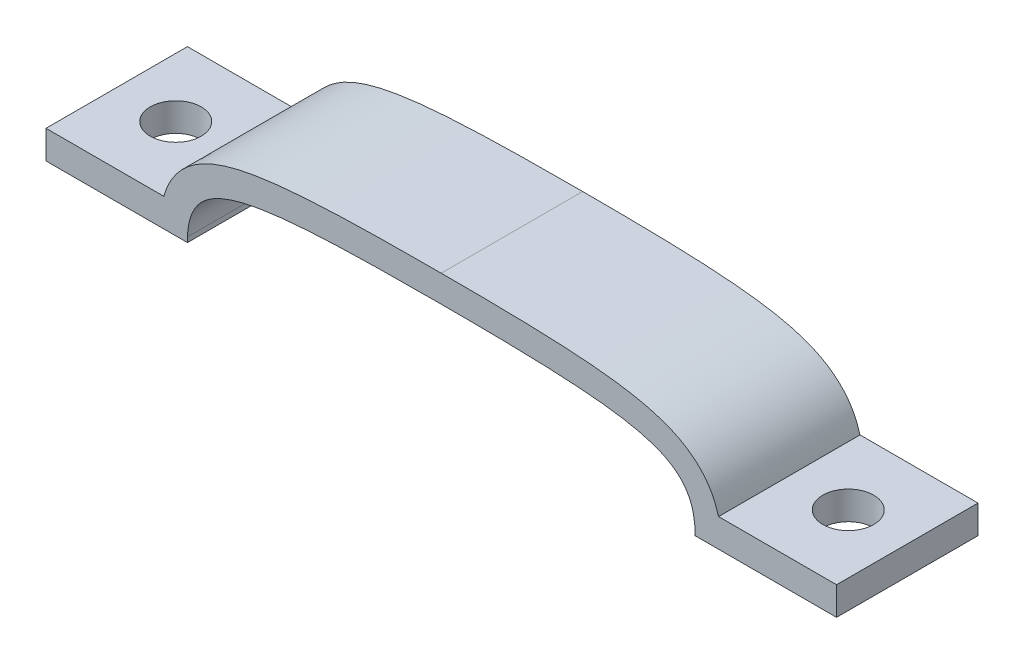
SolidWorks part; units mm, degrees
ref_plane "Front Plane" through (0, 0, 0) normal (0, 0, 1) x (1, 0, 0)
ref_plane "Top Plane" through (0, 0, 0) normal (0, 1, 0) x (1, 0, 0)
ref_plane "Right Plane" through (0, 0, 0) normal (1, 0, 0) x (0, 0, -1)
sketch "Sketch1" plane through (0, 0, 0) normal (0, 0, 1) x (1, 0, 0)
  line L1 (-24.3792, 158.0869) -> (-59.8719, 158.0869) construction
  line L2 (-59.8719, 158.4295) -> (-59.8719, 158.0869) construction
  line L3 (-60.0719, 158.4339) -> (-60.0719, 158.0869)
  line L4 (-60.0719, 158.0869) -> (-70.0719, 158.0869)
  line L5 (-24.1792, 158.0869) -> (-14.1792, 158.0869)
  line L8 (-70.0719, 158.0869) -> (-70.0719, 160.0869)
  line L9 (-22.5208, 160.0869) -> (-14.1792, 160.0869)
  line L10 (-70.0719, 160.0869) -> (-61.7376, 160.0869)
  line L11 (-14.1792, 158.0869) -> (-14.1792, 160.0869)
  spline S2 degree 3 poles (-24.3792, 158.0869) (-24.3792, 158.298) (-24.3948, 158.7203) (-24.4847, 159.3508) (-24.6697, 159.9591) (-25.0702, 160.7158) (-25.8681, 161.4447) (-27.0347, 161.9787) (-28.2637, 162.3243) (-29.5199, 162.5549) (-30.7848, 162.7171) (-32.0543, 162.832) (-33.324, 162.9151) (-34.5929, 162.9748) (-35.8594, 163.0175) (-37.1228, 163.0472) (-38.3821, 163.067) (-39.6369, 163.0793) (-40.8865, 163.0857) (-41.7157, 163.0869) (-42.1292, 163.0869) (-42.1292, 163.0869) knots 0.755163 0.755163 0.755163 0.755163 0.762814 0.770465 0.778117 0.785768 0.80107 0.816372 0.831675 0.846977 0.862279 0.877581 0.892884 0.908186 0.923488 0.938791 0.954093 0.969395 0.984697 1 1 1 1 1 construction
  spline S3 degree 3 poles (-42.1292, 163.0869) (-42.5602, 163.0869) (-43.4199, 163.0856) (-44.7033, 163.0787) (-45.9813, 163.0657) (-47.2546, 163.0449) (-48.5236, 163.0139) (-49.7889, 162.9698) (-51.0508, 162.9085) (-52.309, 162.8238) (-53.5636, 162.7072) (-54.8113, 162.5434) (-56.0496, 162.3114) (-57.2604, 161.9649) (-58.4099, 161.4309) (-59.1956, 160.7049) (-59.591, 159.953) (-59.7742, 159.3479) (-59.8475, 158.8331) (-59.8676, 158.5261) (-59.8719, 158.4295) knots 0.500001 0.500001 0.500001 0.500001 0.515949 0.531896 0.547844 0.563792 0.579739 0.595687 0.611634 0.627582 0.64353 0.659477 0.675425 0.691373 0.70732 0.723268 0.731242 0.739216 0.747189 0.750846 0.750846 0.750846 0.750846 construction
  spline S4 degree 1 poles (-24.1792, 158.0869) (-42.1292, 163.2869) knots 0 0 1 1 construction
  spline S5 degree 1 poles (-42.1292, 163.2869) (-60.0719, 158.4339) knots 0 0 1 1 construction
  spline S6 degree 3 poles (-24.1792, 158.0869) (-24.1792, 158.5234) (-24.2357, 159.392) (-24.7382, 160.6854) (-25.7619, 161.6186) (-26.9688, 162.168) (-28.2199, 162.5198) (-29.9133, 162.8302) (-32.0395, 163.0467) (-34.5867, 163.1831) (-37.1206, 163.2519) (-39.6401, 163.2822) (-41.2977, 163.2869) (-42.1292, 163.2869) knots 0.755163 0.755163 0.755163 0.755163 0.770465 0.785768 0.80107 0.816372 0.831675 0.846977 0.877582 0.908186 0.938791 0.969395 1 1 1 1
  spline S7 degree 3 poles (-42.1292, 163.2869) (-43.8105, 163.2869) (-46.3467, 163.2738) (-49.6708, 163.1825) (-52.1577, 163.0507) (-54.6335, 162.8009) (-56.6878, 162.3976) (-58.2655, 161.7469) (-59.3216, 160.9319) (-59.947, 159.7212) (-60.0527, 158.8638) (-60.0719, 158.4339) knots 0.500001 0.500001 0.500001 0.500001 0.562726 0.594089 0.625452 0.656814 0.688177 0.703858 0.719539 0.735221 0.750902 0.750902 0.750902 0.750902
  spline S8 degree 1 poles (-22.2792, 158.0869) (-42.1292, 165.1869) knots 0 0 1 1 construction
  spline S9 degree 1 poles (-42.1292, 165.1869) (-61.9698, 158.5229) knots 0 0 1 1 construction
  spline S10 degree 3 poles (-22.2792, 158.0869) (-22.2792, 158.3606) (-22.2962, 158.8364) (-22.3756, 159.4478) (-22.4761, 159.9283) (-22.5788, 160.3071) (-22.8045, 160.9303) (-23.2236, 161.7251) (-23.948, 162.5536) (-25.0053, 163.3701) (-26.3471, 163.9717) (-27.8025, 164.3752) (-29.2062, 164.6325) (-30.5609, 164.8055) (-32.3384, 164.9662) (-34.5145, 165.0817) (-37.0857, 165.1517) (-39.6279, 165.1822) (-41.293, 165.1869) (-42.1292, 165.1869) knots 0.755163 0.755163 0.755163 0.755163 0.762814 0.768956 0.770868 0.774694 0.778117 0.785768 0.793419 0.80107 0.816372 0.831675 0.846977 0.862279 0.877582 0.908186 0.938791 0.969395 1 1 1 1 only from (-22.5208, 160.0869) to (-42.1292, 165.1869)
  spline S11 degree 3 poles (-42.1292, 165.1869) (-42.9778, 165.1869) (-44.6782, 165.1819) (-47.2092, 165.1509) (-49.7419, 165.0816) (-52.291, 164.9459) (-54.4551, 164.7315) (-56.2551, 164.418) (-57.6652, 164.0494) (-59.1826, 163.4339) (-60.5111, 162.4374) (-61.3276, 161.228) (-61.6385, 160.4581) (-61.8063, 159.8398) (-61.9215, 159.2218) (-61.9573, 158.8041) (-61.9698, 158.5229) knots 0.500001 0.500001 0.500001 0.500001 0.531357 0.562712 0.594068 0.625424 0.656779 0.672457 0.688135 0.703813 0.71949 0.727329 0.734791 0.73871 0.743007 0.750846 0.750846 0.750846 0.750846 only from (-42.1292, 165.1869) to (-61.7376, 160.0869)
  point P10 (-24.1792, 160.0869)
  point P18 (-60.0719, 160.0869)
  dimension "D2" = 10
  dimension "D4" = 2
  dimension "D1" = 0.2
  dimension "D3" = 2.1
extrude "Boss-Extrude1" add sketch "Sketch1" along normal blind 10
sketch "Sketch2" plane through (0, 158.0869, 0) normal (0, -1, 0) x (-1, 0, 0)
  point P10 (18.35, -5)
  point P13 (65.9011, -5)
hole_wizard "M3 Clearance Hole1" positions "Sketch2" profile "Sketch3" hole size "M3" standard "ANSI Metric" end condition through all
sketch "Sketch3" plane through (-18.35, 158.0869, 5) normal (1, 0, 0) x (0, 0, -1)
  line L0 (0, 0) -> (0, 7.1)
  line L1 (0, 7.1) -> (1.8, 7.1)
  line L2 (1.8, 7.1) -> (1.8, 0)
  line L5 (1.8, 0) -> (0, 0)
  line L11 (0, -6.35) -> (0, 107.95) construction
  dimension "Thru Hole Dia." = 3.6
  dimension "Thru Hole Depth" = 7.1
